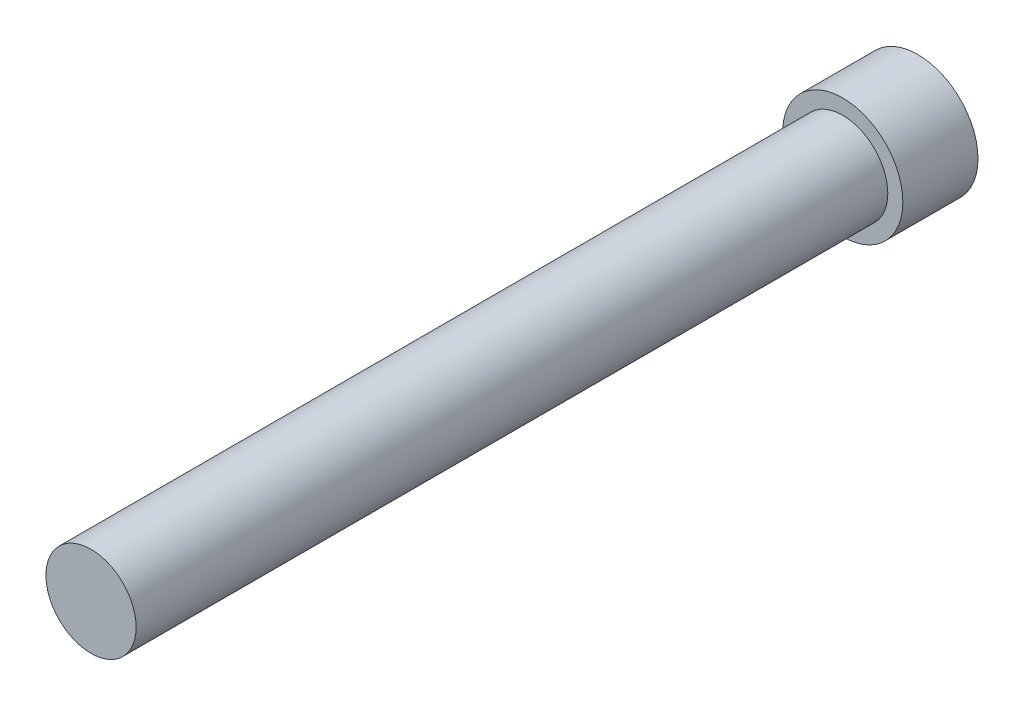
SolidWorks part; units mm, degrees
ref_plane "前视基准面" through (0, 0, 0) normal (0, 0, 1) x (1, 0, 0)
ref_plane "上视基准面" through (0, 0, 0) normal (0, 1, 0) x (1, 0, 0)
ref_plane "右视基准面" through (0, 0, 0) normal (1, 0, 0) x (0, 0, -1)
sketch "草图1" plane through (0, 0, 0) normal (0, 0, 1) x (1, 0, 0)
  line L1 (-0.9563, 1.0811) -> (-1.4144, -0.2877)
  line L2 (-1.4144, -0.2877) -> (-0.4581, -1.3688)
  line L3 (-0.4581, -1.3688) -> (0.9563, -1.0811)
  line L4 (0.9563, -1.0811) -> (1.4144, 0.2877)
  line L5 (1.4144, 0.2877) -> (0.4581, 1.3688)
  line L6 (0.4581, 1.3688) -> (-0.9563, 1.0811)
  circle A0 centre (0, 0) radius 2
  circle A1 centre (0, 0) radius 1.25 construction
  point P3 (1.1854, -0.3967)
  dimension "D1" = 4
  dimension "D2" = 2.5
extrude "凸台-拉伸1" add sketch "草图1" along normal blind 2.5
ref_plane "基准面1" through (0, 0, 2.5) normal (0, 0, 1) x (1, 0, 0)
sketch "草图2" plane through (0, 0, 2.5) normal (0, 0, 1) x (1, 0, 0)
  circle A0 centre (0, 0) radius 1.5
  dimension "D1" = 3
extrude "凸台-拉伸2" add sketch "草图2" along normal blind 25
